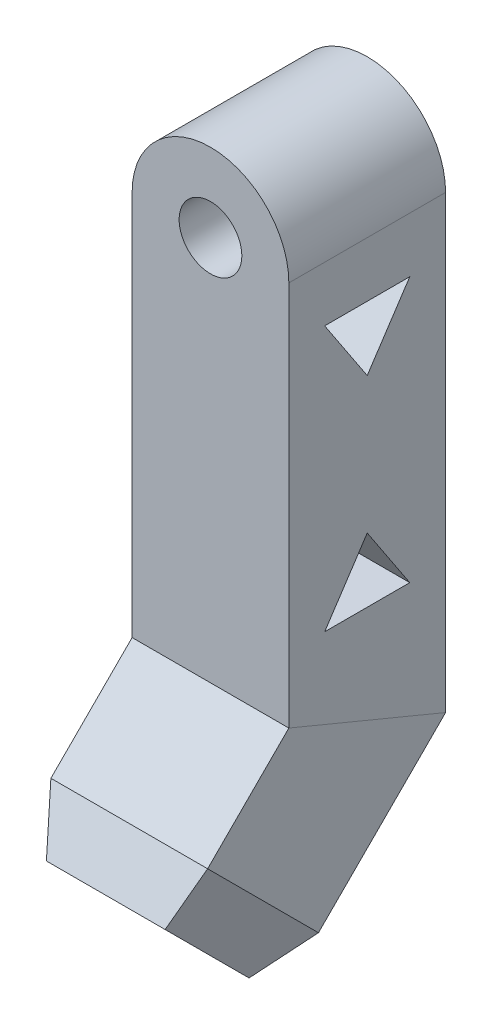
SolidWorks part; units mm, degrees
ref_plane "Front Plane" through (0, 0, 0) normal (0, 0, 1) x (1, 0, 0)
ref_plane "Top Plane" through (0, 0, 0) normal (0, 1, 0) x (1, 0, 0)
ref_plane "Right Plane" through (0, 0, 0) normal (1, 0, 0) x (0, 0, -1)
ref_plane "Plane2" through (0, 96.393, 0) normal (0, 1, 0) x (1, 0, 0)
sketch "Sketch10" plane through (0, 0, 0) normal (1, 0, 0) x (0, 0, -1)
  line L0 (0, 96.393) -> (0, -5.207)
  line L1 (55, 96.393) -> (-55, 96.393) construction
  line L2 (0, -5.207) -> (-25.3243, -30.5313)
  dimension "D1" = 101.6
  dimension "D2" = 35.814
  dimension "D3" = 135
sketch "Sketch11" plane through (0, 96.393, 0) normal (0, 1, 0) x (1, 0, 0)
  line L1 (-19.05, -19.05) -> (19.05, -19.05)
  line L2 (-19.05, -19.05) -> (-19.05, 19.05)
  line L3 (-19.05, 19.05) -> (19.05, 19.05)
  line L4 (19.05, -19.05) -> (19.05, 19.05)
  line L5 (-19.05, -19.05) -> (19.05, 19.05) construction
  line L6 (-19.05, 19.05) -> (19.05, -19.05) construction
  point P0 (0, 0)
  dimension "D1" = 38.1
sweep "Sweep1" add profiles "Sketch11" path "Sketch10"
sketch "Sketch12" plane through (0, -27.9278, 27.9278) normal (0, -0.7071, 0.7071) x (1, 0, 0)
  line L4 (19.05, -22.7319) -> (19.05, 15.3681)
  line L5 (19.05, -22.7319) -> (19.05, 15.3681)
  line L6 (19.05, 15.3681) -> (-19.05, 15.3681)
  line L7 (19.05, 15.3681) -> (-19.05, 15.3681)
  line L8 (-19.05, 15.3681) -> (-19.05, -22.7319)
  line L9 (-19.05, 15.3681) -> (-19.05, -22.7319)
  line L10 (-19.05, -22.7319) -> (19.05, -22.7319)
  line L11 (-19.05, -22.7319) -> (19.05, -22.7319)
  dimension "D1" = 0
extrude "Boss-Extrude5" add sketch "Sketch12" along normal blind 12.7 draft 20
sketch "Sketch13" plane through (0, 0, -19.05) normal (0, 0, -1) x (-1, 0, 0)
  line L0 (20.955, 96.393) -> (-20.955, 96.393) construction
  line L1 (0, 31.8146) -> (0, -31.8146) construction
  line L2 (-19.05, 96.393) -> (19.05, 96.393)
  arc A0 (19.05, 96.393) -> (-19.05, 96.393) centre (0, 96.393) ccw
  dimension "D1" = 38.1
extrude "Boss-Extrude6" add sketch "Sketch13" against normal up to surface (38.1 mm away) up to face at (0, 49.5384, 19.05)
sketch "Sketch14" plane through (0, 0, 19.05) normal (0, 0, 1) x (1, 0, 0)
  circle A0 centre (0, 96.393) radius 7.62
  arc A1 (19.05, 96.393) -> (-19.05, 96.393) centre (0, 96.393) ccw construction
  dimension "D1" = 15.24
extrude "Cut-Extrude2" cut sketch "Sketch14" against normal blind 38.1
sketch "Sketch15" plane through (0, -36.9081, 36.9081) normal (0, -0.7071, 0.7071) x (1, 0, 0)
  line L1 (-14.4276, 10.7457) -> (14.4276, -18.1095) construction
  line L2 (-14.4276, -18.1095) -> (14.4276, 10.7457) construction
  circle A2 centre (0, -3.6819) radius 12.065
  dimension "D1" = 24.13
extrude "Cut-Extrude3" cut sketch "Sketch15" against normal blind 12.7
sketch "Sketch16" plane through (-19.05, 0, 0) normal (-1, 0, 0) x (0, 0, 1)
  line L3 (-19.05, 50.8) -> (19.05, 50.8) construction
  line L4 (-10.3452, 83) -> (10.3452, 83)
  line L5 (10.3452, 83) -> (0, 67.3767)
  line L13 (-19.05, 96.393) -> (-19.05, -13.0978) construction
  line L14 (19.05, 96.393) -> (19.05, 2.6838) construction
  line L18 (-10.3452, 83) -> (0, 67.3767)
  line L19 (10.3452, 18.6) -> (0, 34.2233)
  line L20 (-10.3452, 18.6) -> (10.3452, 18.6)
  line L21 (-10.3452, 18.6) -> (0, 34.2233)
  point P9 (0, 50.8)
  dimension "D1" = 20.6903
  dimension "D2" = 56.489
  dimension "D3" = 67.3767
  dimension "D6" = 38.1
  dimension "D7" = 50.8
extrude "Cut-Extrude4" cut sketch "Sketch16" against normal blind 38.1
